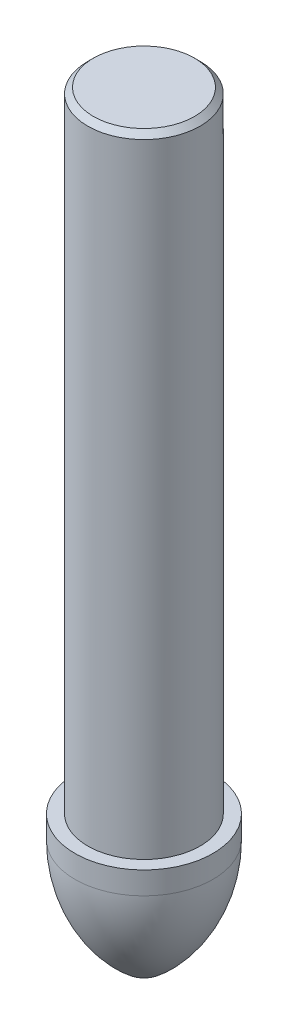
SolidWorks part; units mm, degrees
material "1.2316 (X36CrMo17)"
ref_plane "Front Plane" through (0, 0, 0) normal (0, 0, 1) x (1, 0, 0)
ref_plane "Top Plane" through (0, 0, 0) normal (0, 1, 0) x (1, 0, 0)
ref_plane "Right Plane" through (0, 0, 0) normal (1, 0, 0) x (0, 0, -1)
sketch "Sketch1" plane through (0, 0, 0) normal (0, 0, 1) x (1, 0, 0)
  line L0 (0, 0) -> (0, -39.3174) construction
  line L1 (0, 0) -> (2.5, 0)
  line L2 (2.5, 0) -> (2.5, -28)
  line L3 (2.5, -28) -> (3.07, -28)
  line L4 (3.07, -28) -> (3.07, -29)
  line L5 (3.07, -29) -> (-3.07, -29) construction
  line L6 (0, -34.0562) -> (0, 0)
  arc A1 (0.7848, -33.7792) -> (3.07, -29) centre (-3.07, -29) ccw
  arc A2 (0, -34.0562) -> (0.7848, -33.7792) centre (0, -32.8062) ccw
  arc A3 (0, -31.5562) -> (0, -34.0562) centre (0, -32.8062) ccw construction
  arc A4 (0.7848, -33.7792) -> (0, -31.5562) centre (0, -32.8062) ccw construction
  arc A5 (0, -34.3174) -> (0.7848, -33.7792) centre (-3.07, -29) ccw construction
  dimension "D6" = 2.5
  dimension "D1" = 6.14
  dimension "PilotDiameter" = 6.14
  dimension "D2" = 5
  dimension "D4" = 6.14
  dimension "ShankLength" = 29
  dimension "D3" = 1
  dimension "D5" = 5
revolve "Revolve1" add sketch "Sketch1" angle 360 about L0
chamfer "Chamfer1" distance 0.25 angle 45 1 edges at (-2.5, 0, 0)
cosmetic thread "Cosmetic Thread2"
equation "\"D4@Sketch1\" = \"PilotDiameter@Sketch1\""
equation "\"Pierce Punch Diameter\" = 6.2"
equation "\"PilotDiameter@Sketch1\" = \"Pierce Punch Diameter\" - 0.03 * 2"
equation "\"Material Thickness\" = 2mm"
equation "\"Punch Height\" = 20mm"
equation "\"ShankLength@Sketch1\" = \"Punch Height\" + \"Thread into Punch Holder\" + \"Pilot Engagement Length\""
equation "\"Thread into Punch Holder\" = 8mm"
equation "\"Pilot Engagement Length\"= \"Material Thickness\" * 0.5"
